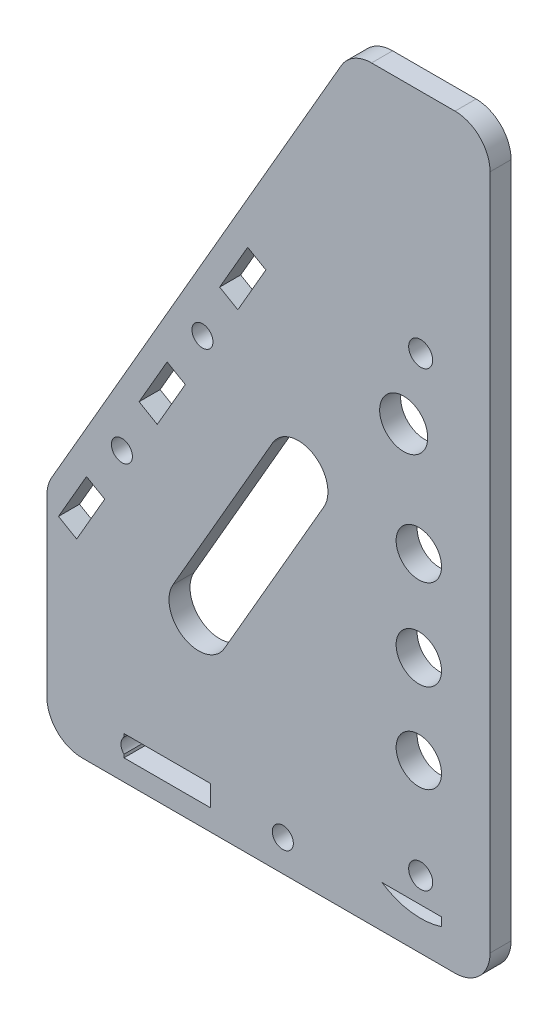
SolidWorks part; units mm, degrees
material "Balsa"
ref_plane "Front" through (0, 0, 0) normal (0, 0, 1) x (1, 0, 0)
ref_plane "Top" through (0, 0, 0) normal (0, 1, 0) x (1, 0, 0)
ref_plane "Right" through (0, 0, 0) normal (1, 0, 0) x (0, 0, -1)
sketch "Sketch1" plane through (0, 0, 0) normal (0, 0, 1) x (1, 0, 0)
  line L0 (-0.006, 51.9848) -> (-0.006, -1.6689) construction
  line L1 (9.8948, 51.9848) -> (9.8948, -1.6689)
  line L2 (-9.9068, 51.9848) -> (-9.9068, -1.6689)
  line L3 (-9.9068, -1.6689) -> (-9.9068, -15.8948)
  line L4 (-9.9068, -15.8948) -> (9.8948, -15.8948)
  line L5 (9.8948, -15.8948) -> (9.8948, -1.6689)
  line L6 (-9.9068, -15.8948) -> (-53.3543, -15.8948)
  line L7 (-53.3543, -15.8948) -> (-53.3543, -9.8948)
  line L8 (-53.3543, -9.8948) -> (-53.3543, 15.4081)
  line L9 (-53.3543, -11.3948) -> (9.8948, -11.3948) construction
  line L10 (2.9845, -12.8948) -> (2.9845, -9.8948)
  line L11 (2.9845, -12.8948) -> (45.5654, -12.8948) construction
  line L12 (-53.3543, 15.4081) -> (-9.9068, 90.6612)
  line L13 (-42.3537, -9.8948) -> (-29.9887, -9.8948)
  line L14 (-42.3537, -9.8948) -> (-42.3537, -12.8948)
  line L15 (-42.3537, -12.8948) -> (-29.9887, -12.8948)
  line L16 (-29.9887, -9.8948) -> (-29.9887, -12.8948)
  line L17 (-9.3805, -9.8948) -> (2.9845, -9.8948)
  line L18 (-9.3805, -9.8948) -> (-9.3805, -12.8948)
  line L19 (-9.3805, -12.8948) -> (2.9845, -12.8948)
  line L20 (2.9845, -9.8948) -> (2.9845, -12.8948) construction
  line L21 (-53.3543, -9.8948) -> (-53.3543, -12.8948) construction
  line L22 (-53.3543, -9.8948) -> (-53.3543, -12.8948) construction
  line L23 (-19.6846, -9.8948) -> (-19.6846, -12.8948) construction
  line L24 (-9.9068, 51.9848) -> (-9.9068, 90.6612) construction
  line L26 (9.8948, 52.4446) -> (9.8948, -0.4538) construction
  line L28 (-9.9068, 90.6612) -> (9.8948, 90.6612)
  line L29 (9.8948, 90.6612) -> (9.8948, 51.9848)
  arc A0 (9.8948, 51.9848) -> (-9.9068, 51.9848) centre (-0.006, 51.9848) ccw
  arc A1 (-9.9068, -1.6689) -> (9.8948, -1.6689) centre (-0.006, -1.6689) ccw
  circle A4 centre (-41.2832, -11.3948) radius 1.5
  circle A5 centre (-19.6846, -11.3948) radius 1.5
  point P2 (-0.006, 25.1579)
  point P16 (-5.5161, -9.8948)
  dimension "D2" = 3
  dimension "D3" = 3
  dimension "D1" = 6
  dimension "D4" = 150
extrude "Boss-Extrude1" add sketch "Sketch1" along normal blind 3 contours L2 A1 L1 A0 | A0 L12 L8 L7 L6 L3 L2 A4 L13 L16 L15 L14 | A1 L3 L4 L5 L17 L10 L19 L18 A5 | A1 L3 L17
sketch "Sketch2" [suppressed] plane through (0, 0, 0) normal (0, 0, 1) x (1, 0, 0)
  line L0 (-2.4122, 37.5987) -> (-2.4121, 31.4011) construction
  line L1 (-2.8138, 11.0925) -> (8.2096, 11.0925)
  line L2 (-2.8138, 11.0925) -> (-2.8138, 20.4906)
  line L3 (-2.8138, 20.4906) -> (8.2096, 20.4906)
  line L4 (8.2096, 11.0925) -> (8.2096, 20.4906)
  line L5 (-1.1628, 22.2368) -> (1.3263, 22.2368)
  line L6 (-1.1628, 22.2368) -> (-1.1628, 27.2405)
  line L7 (-1.1628, 27.2405) -> (1.3263, 27.2405)
  line L8 (1.3263, 22.2368) -> (1.3263, 27.2405)
  line L9 (-2.4122, 37.5987) -> (-2.4121, 31.4011)
  line L10 (-2.4121, 31.4011) -> (-1.6501, 30.6391)
  line L11 (-1.6501, 30.6391) -> (0.2295, 30.6391)
  line L12 (0.2295, 30.6391) -> (0.2294, 38.3607)
  line L13 (0.2294, 38.3607) -> (-1.6502, 38.3607)
  line L14 (-1.6502, 38.3607) -> (-2.4122, 37.5987)
  circle A1 centre (-0.0111, -6.2753) radius 1.7144
  circle A2 centre (-0.0115, 58.266) radius 1.7144
  circle A3 centre (-2.433, 48.3606) radius 3.4289
  circle A4 centre (1.3263, 2.6405) radius 2.2226
extrude "Cut-Extrude2" [suppressed] cut sketch "Sketch2" along normal through all
sketch "Sketch3" plane through (0, 0, 0) normal (0, 0, 1) x (1, 0, 0)
  circle A0 centre (-0.0113, -6.2752) radius 1.7144
  circle A1 centre (-0.2773, 7.8155) radius 3.2384
  circle A2 centre (-0.2773, 20.5155) radius 3.2384
  circle A3 centre (-0.2773, 33.3805) radius 3.2384
  circle A4 centre (-2.4363, 48.3419) radius 3.4289
  circle A5 centre (-0.0113, 58.2661) radius 1.7144
extrude "Cut-Extrude4" cut sketch "Sketch3" along normal through all
sketch "Sketch4" plane through (0, 0, 0) normal (0, 0, 1) x (1, 0, 0)
  line L0 (-53.3543, 6.4081) -> (-4.7107, 90.6612) construction
  line L1 (-53.3543, 15.4081) -> (-9.9068, 90.6612) construction
  line L2 (-9.9068, 90.6612) -> (9.8948, 90.6612) construction
  line L3 (-40.2009, 32.1904) -> (-36.2009, 39.1186)
  line L4 (-36.2009, 39.1186) -> (-33.6028, 37.6186)
  line L5 (-33.6028, 37.6186) -> (-37.6028, 30.6904)
  line L6 (-37.6028, 30.6904) -> (-40.2009, 32.1904)
  line L7 (-24.7009, 59.0372) -> (-28.7009, 52.109)
  line L8 (-28.7009, 52.109) -> (-26.1028, 50.609)
  line L9 (-26.1028, 50.609) -> (-22.1028, 57.5372)
  line L10 (-22.1028, 57.5372) -> (-24.7009, 59.0372)
  line L11 (-51.7009, 12.2718) -> (-47.7009, 19.2)
  line L12 (-47.7009, 19.2) -> (-45.1028, 17.7)
  line L13 (-45.1028, 17.7) -> (-49.1028, 10.7718)
  line L14 (-49.1028, 10.7718) -> (-51.7009, 12.2718)
  line L15 (-40.2009, 32.1904) -> (-33.6028, 37.6186) construction
  line L16 (-53.3543, -15.8948) -> (-53.3543, 15.4081) construction
  circle A0 centre (-42.6518, 24.9452) radius 1.5
  circle A1 centre (-31.1518, 44.8638) radius 1.5
  point P22 (-36.9018, 34.9045)
  point P30 (-50.4018, 11.5218)
  dimension "D6" = 3
  dimension "D2" = 3
  dimension "D3" = 8
  dimension "D4" = 15
  dimension "D5" = 15
  dimension "D7" = 11.5
  dimension "D8" = 11.5
  dimension "D1" = 4.5
extrude "Cut-Extrude5" cut sketch "Sketch4" along normal through all
sketch "Sketch5" plane through (0, 0, 3) normal (0, 0, 1) x (1, 0, 0)
  line L0 (-31.7034, 9.8811) -> (-17.4767, 34.5224) construction
  line L1 (-35.3666, 11.9961) -> (-21.1399, 36.6373)
  line L2 (-28.0401, 7.7662) -> (-13.8135, 32.4074)
  line L3 (-53.3543, 15.4081) -> (-9.9068, 90.6612) construction
  arc A0 (-35.3666, 11.9961) -> (-28.0401, 7.7662) centre (-31.7034, 9.8811) ccw
  arc A1 (-13.8135, 32.4074) -> (-21.1399, 36.6373) centre (-17.4767, 34.5224) ccw
  point P2 (-24.59, 22.2018)
extrude "CableHole" cut sketch "Sketch5" against normal through all both and the other way through all
fillet "Fillet1" radius 5 5 edges at (-53.3543, -15.8948, 1.5) (-53.3543, 15.4081, 1.5) (-9.9068, 90.6612, 1.5) (9.8948, -15.8948, 1.5) (9.8948, 90.6612, 1.5)
equation "\"D8@Sketch4\"=(\"D4@Sketch4\"+\"D3@Sketch4\")/2"
equation "\"D7@Sketch4\"=\"D8@Sketch4\""
equation "\"D5@Sketch4\"=\"D4@Sketch4\""
